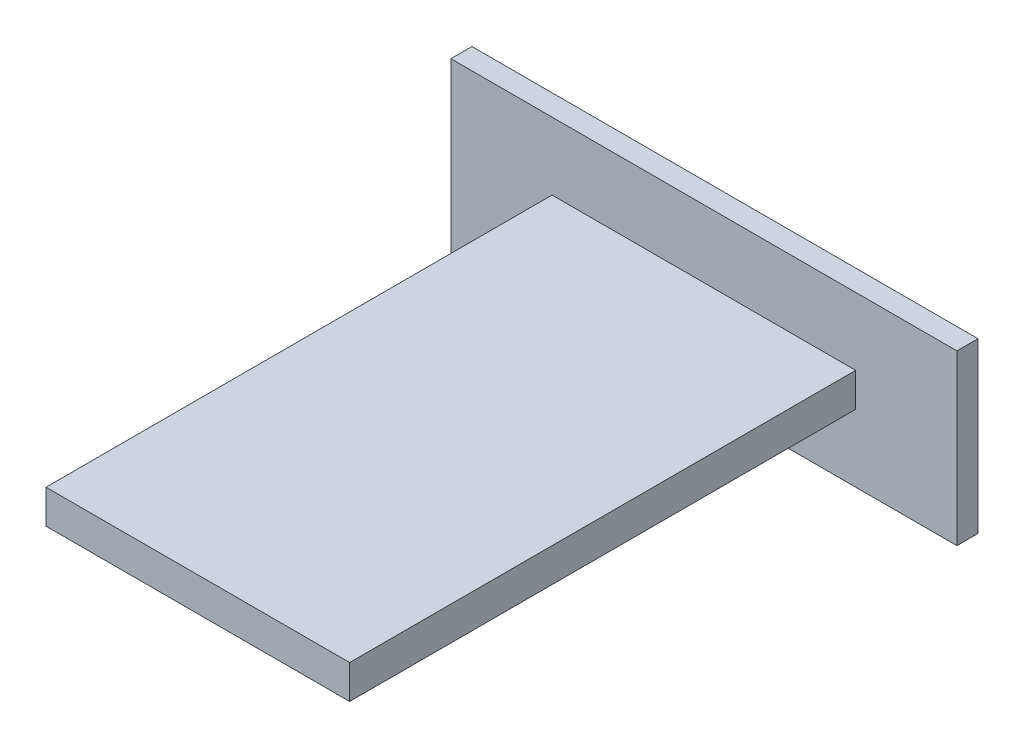
SolidWorks part; units mm, degrees
ref_plane "Front Plane" through (0, 0, 0) normal (0, 0, 1) x (1, 0, 0)
ref_plane "Top Plane" through (0, 0, 0) normal (0, 1, 0) x (1, 0, 0)
ref_plane "Right Plane" through (0, 0, 0) normal (1, 0, 0) x (0, 0, -1)
sketch "Sketch1" plane through (0, 0, 0) normal (0, 1, 0) x (1, 0, 0)
  line L1 (-9, -15) -> (9, -15)
  line L2 (-9, -15) -> (-9, 15)
  line L3 (-9, 15) -> (9, 15)
  line L4 (9, -15) -> (9, 15)
  line L5 (-9, -15) -> (9, 15) construction
  line L6 (-9, 15) -> (9, -15) construction
  point P0 (0, 0)
  dimension "D1" = 18
  dimension "D2" = 30
extrude "Boss-Extrude1" add sketch "Sketch1" along normal blind 2
sketch "Sketch2" plane through (0, 0, -15) normal (0, 0, -1) x (-1, 0, 0)
  line L5 (-9, 1) -> (9, 1) construction
  line L6 (-9, 2) -> (-9, 0) construction
  line L7 (9, 2) -> (9, 0) construction
  line L9 (-15, -4) -> (15, -4)
  line L10 (-15, -4) -> (-15, 6)
  line L11 (-15, 6) -> (15, 6)
  line L12 (15, -4) -> (15, 6)
  line L13 (-15, -4) -> (15, 6) construction
  line L14 (-15, 6) -> (15, -4) construction
  point P7 (0, 1)
  dimension "D1" = 6
  dimension "D2" = 4
extrude "Boss-Extrude2" add sketch "Sketch2" along normal blind 1.25
